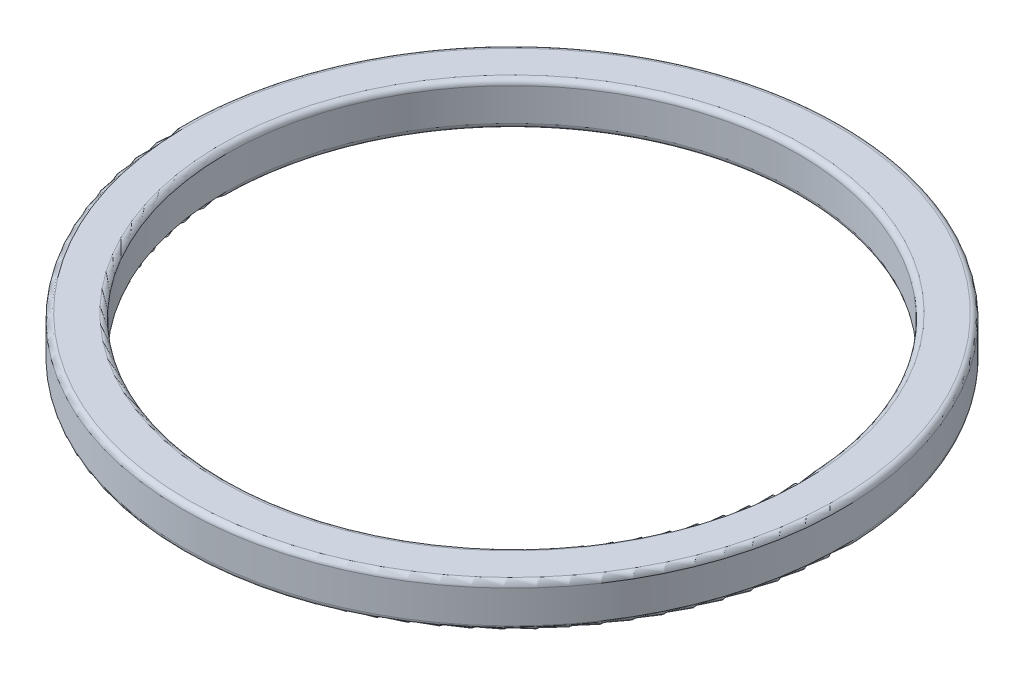
SolidWorks part; units mm, degrees
ref_plane "Front Plane" through (0, 0, 0) normal (0, 0, 1) x (1, 0, 0)
ref_plane "Top Plane" through (0, 0, 0) normal (0, 1, 0) x (1, 0, 0)
ref_plane "Right Plane" through (0, 0, 0) normal (1, 0, 0) x (0, 0, -1)
sketch "Sketch1" plane through (0, 0, 0) normal (0, 1, 0) x (1, 0, 0)
  circle A0 centre (0, 0) radius 10.5
  dimension "D1" = 21
extrude "Extrude-Thin1" add sketch "Sketch1" along normal blind 1.6 thin
fillet "Fillet1" radius 0.2 4 edges at (12.1, 0, 0) (12.1, 1.6, 0) (0, 0, 10.5) (0, 1.6, 10.5)
